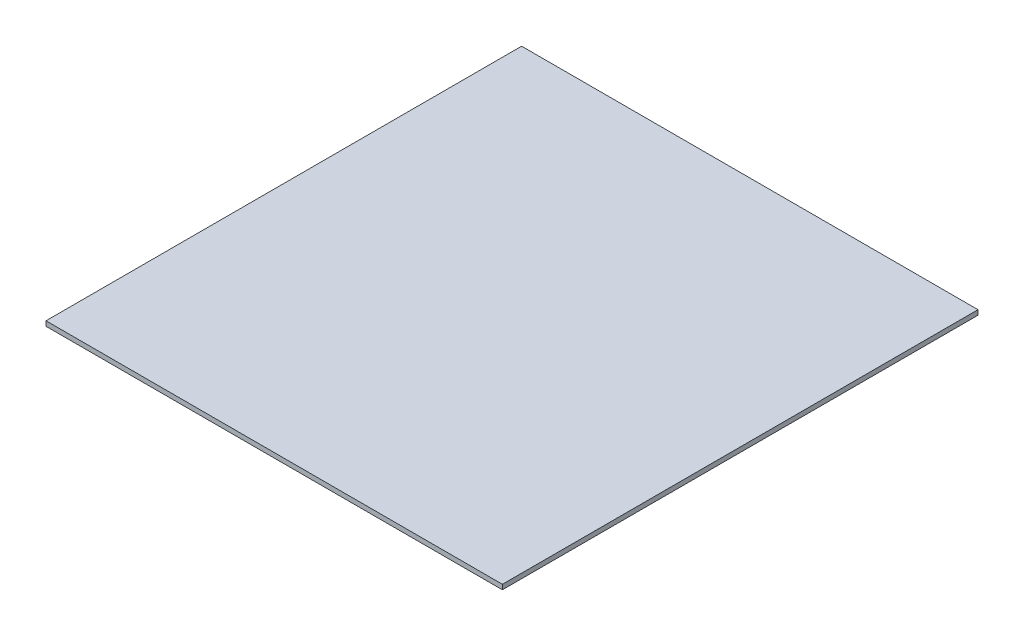
SolidWorks part; units mm, degrees
ref_plane "Front Plane" through (0, 0, 0) normal (0, 0, 1) x (1, 0, 0)
ref_plane "Top Plane" through (0, 0, 0) normal (0, 1, 0) x (1, 0, 0)
ref_plane "Right Plane" through (0, 0, 0) normal (1, 0, 0) x (0, 0, -1)
sketch "Sketch1" plane through (0, 0, 0) normal (0, 1, 0) x (1, 0, 0)
  line L1 (-95, -99) -> (95, -99)
  line L2 (-95, -99) -> (-95, 99)
  line L3 (-95, 99) -> (95, 99)
  line L4 (95, -99) -> (95, 99)
  line L5 (-95, -99) -> (95, 99) construction
  line L6 (-95, 99) -> (95, -99) construction
  point P0 (0, 0)
  dimension "D1" = 190
  dimension "D2" = 198
extrude "Boss-Extrude1" add sketch "Sketch1" along normal mid plane 2
